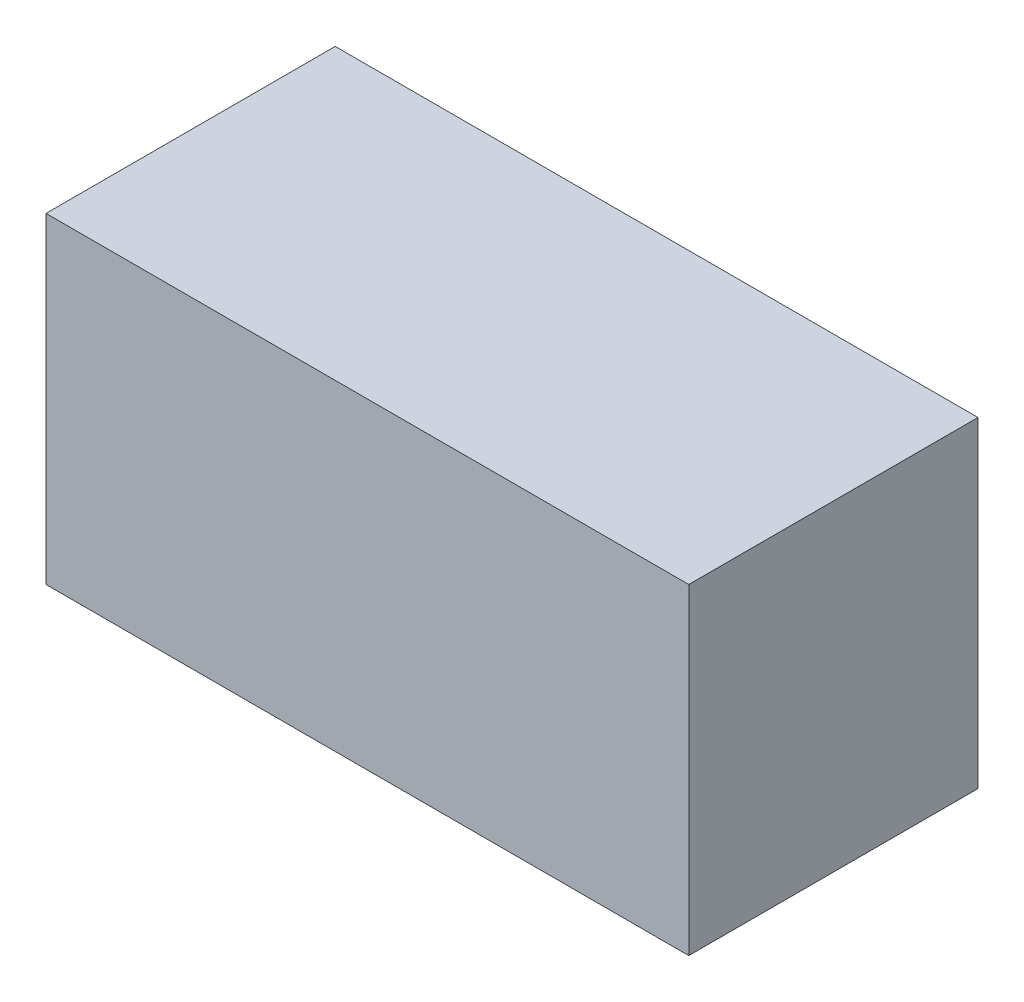
SolidWorks part; units mm, degrees
ref_plane "前视基准面" through (0, 0, 0) normal (0, 0, 1) x (1, 0, 0)
ref_plane "上视基准面" through (0, 0, 0) normal (0, 1, 0) x (1, 0, 0)
ref_plane "右视基准面" through (0, 0, 0) normal (1, 0, 0) x (0, 0, -1)
sketch "草图1" plane through (0, 0, 0) normal (0, 0, 1) x (1, 0, 0)
  line L0 (-1, -0.5) -> (-1, 0.5)
  line L1 (-1, 0.5) -> (1, 0.5)
  line L2 (1, 0.5) -> (1, -0.5)
  line L3 (1, -0.5) -> (-1, -0.5)
extrude "Component_Outline" add sketch "草图1" along normal blind 0.9 separate body
sketch3d "3D草图1"
  line L0 (0, 0, 0) -> (1, 0, 0)
  line L1 (0, 0, 0) -> (0, 1, 0)
  line L2 (0, 0, 0) -> (0, 0, 1)
  point P0 (0, 0, 0)
